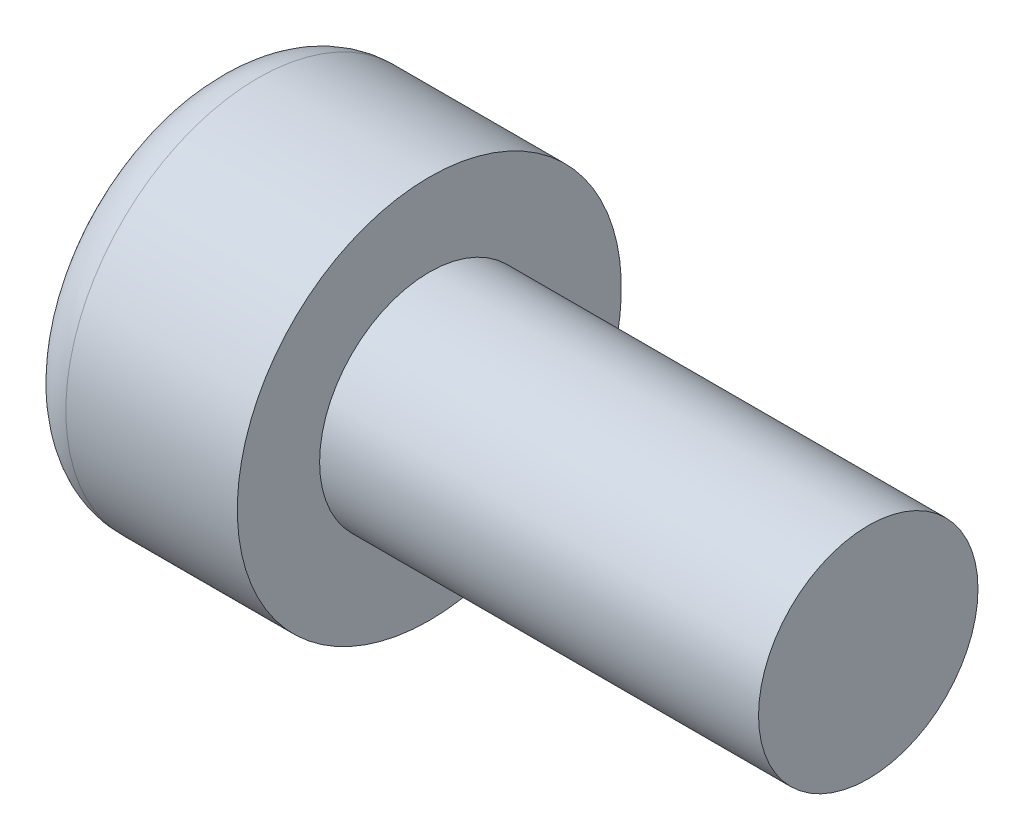
SolidWorks part; units mm, degrees
material "Plain Carbon Steel"
ref_plane "Front Plane" through (0, 0, 0) normal (0, 0, 1) x (1, 0, 0)
ref_plane "Top Plane" through (0, 0, 0) normal (0, 1, 0) x (1, 0, 0)
ref_plane "Right Plane" through (0, 0, 0) normal (1, 0, 0) x (0, 0, -1)
sketch "Sketch1" plane through (0, 0, 0) normal (0, 0, 1) x (1, 0, 0)
  line L0 (0, 0) -> (0, 2.625)
  line L1 (0.875, 3.5) -> (4, 3.5)
  line L2 (4, 3.5) -> (4, 2)
  line L3 (4, 2) -> (12, 2)
  line L4 (12, 2) -> (12, 0)
  line L5 (12, 0) -> (0, 0) construction
  line L6 (0.875, 2.625) -> (0.875, 1.75) construction
  line L7 (0.875, 1.75) -> (0.875, 0.875) construction
  line L8 (0.875, 0.875) -> (0.875, 0) construction
  line L9 (0.875, 3.5) -> (0.875, 2.625) construction
  line L10 (0, 0) -> (12, 0)
  arc A0 (0, 2.625) -> (0.875, 3.5) centre (0.875, 2.625) cw
  dimension "D1" = 4
  dimension "D2" = 7
  dimension "D3" = 4
  dimension "D4" = 8
revolve "Revolve1" add sketch "Sketch1" angle 360 about L10
sketch "Sketch2" plane through (0, 0, 0) normal (-1, 0, 0) x (0, 0, 1)
  line L1 (0, 1.7321) -> (-1.5, 0.866)
  line L2 (-1.5, 0.866) -> (-1.5, -0.866)
  line L3 (-1.5, -0.866) -> (0, -1.7321)
  line L4 (0, -1.7321) -> (1.5, -0.866)
  line L5 (1.5, -0.866) -> (1.5, 0.866)
  line L6 (1.5, 0.866) -> (0, 1.7321)
  circle A0 centre (0, 0) radius 1.5 construction
  dimension "D1" = 3
extrude "Cut-Extrude1" cut sketch "Sketch2" against normal blind 2
